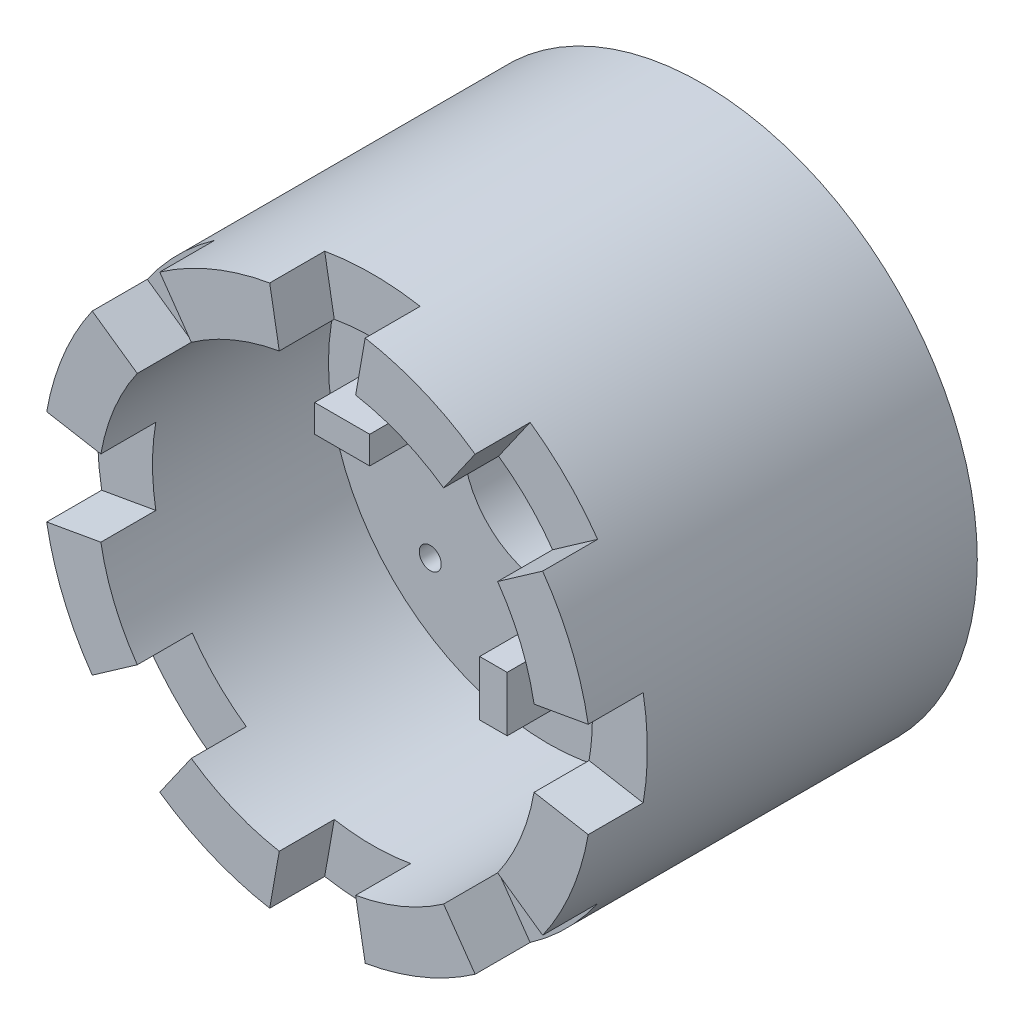
SolidWorks part; units mm, degrees
ref_plane "Alzado" through (0, 0, 0) normal (0, 0, 1) x (1, 0, 0)
ref_plane "Planta" through (0, 0, 0) normal (0, 1, 0) x (1, 0, 0)
ref_plane "Vista lateral" through (0, 0, 0) normal (1, 0, 0) x (0, 0, -1)
sketch "Croquis1" plane through (0, 0, 0) normal (0, 0, 1) x (1, 0, 0)
  circle A0 centre (0, 0) radius 50
  circle A1 centre (0, 0) radius 15.5
  point P4 (0, 0)
  dimension "D1" = 100
  dimension "D2" = 31
extrude "Saliente-Extruir1" add sketch "Croquis1" along normal blind 70
sketch "Croquis2" plane through (0, 0, 70) normal (0, 0, 1) x (1, 0, 0)
  circle A0 centre (0, 0) radius 40
  dimension "D1" = 80
extrude "Cortar-Extruir1" cut sketch "Croquis2" against normal blind 32
sketch "Croquis3" plane through (0, 0, 0) normal (0, 0, -1) x (-1, 0, 0)
  circle A0 centre (0, 0) radius 17.5
  dimension "D1" = 35
extrude "Cortar-Extruir2" cut sketch "Croquis3" against normal blind 10
sketch "Croquis4" plane through (0, 0, 38) normal (0, 0, 1) x (1, 0, 0)
  line L1 (-2.5, 32.5) -> (2.5, 32.5)
  line L2 (-2.5, 32.5) -> (-2.5, 22.5)
  line L3 (-2.5, 22.5) -> (2.5, 22.5)
  line L4 (2.5, 32.5) -> (2.5, 22.5)
  line L5 (-2.5, 32.5) -> (2.5, 22.5) construction
  line L6 (-2.5, 22.5) -> (2.5, 32.5) construction
  line L7 (32.5, -2.5) -> (22.5, -2.5)
  line L8 (32.5, -2.5) -> (32.5, 2.5)
  line L9 (32.5, 2.5) -> (22.5, 2.5)
  line L10 (22.5, -2.5) -> (22.5, 2.5)
  line L11 (32.5, -2.5) -> (22.5, 2.5) construction
  line L12 (32.5, 2.5) -> (22.5, -2.5) construction
  line L13 (2.5, -32.5) -> (-2.5, -32.5)
  line L14 (2.5, -32.5) -> (2.5, -22.5)
  line L15 (2.5, -22.5) -> (-2.5, -22.5)
  line L16 (-2.5, -32.5) -> (-2.5, -22.5)
  line L17 (2.5, -32.5) -> (-2.5, -22.5) construction
  line L18 (2.5, -22.5) -> (-2.5, -32.5) construction
  line L19 (-32.5, -2.5) -> (-22.5, -2.5)
  line L20 (-32.5, -2.5) -> (-32.5, 2.5)
  line L21 (-32.5, 2.5) -> (-22.5, 2.5)
  line L22 (-22.5, -2.5) -> (-22.5, 2.5)
  line L23 (-32.5, -2.5) -> (-22.5, 2.5) construction
  line L24 (-32.5, 2.5) -> (-22.5, -2.5) construction
  circle A0 centre (0, 0) radius 40
  circle A1 centre (0, 0) radius 27.5
  point P4 (0, 27.5)
  point P9 (27.5, 0)
  point P14 (0, -27.5)
  point P19 (-27.5, 0)
  circle M10 centre (0, 0) radius 15.5
  circle M11 centre (0, 0) radius 40
  dimension "D1" = 80
  dimension "D2" = 55
  dimension "D3" = 10
  dimension "D4" = 5
  dimension "D5" = 5
  dimension "D6" = 10
  dimension "D7" = 5
  dimension "D8" = 10
  dimension "D9" = 5
  dimension "D10" = 10
extrude "Cortar-Extruir3" cut sketch "Croquis4" against normal blind 10 contours A1 L9 L8 L7 L14 L13 L16 L19 L20 L21 L2 L1 L4 M11 | L9 A1 L4 L3 L2 L21 L22 L19 L16 L15 L14 L7 L10 M10
sketch "Croquis5" plane through (0, 0, 28) normal (0, 0, 1) x (1, 0, 0)
  line L0 (0, 0) -> (28.2843, 28.2843) construction
  circle A0 centre (21.487, 21.487) radius 2
  circle A1 centre (21.487, -21.487) radius 2
  circle A2 centre (-21.487, -21.487) radius 2
  circle A3 centre (-21.487, 21.487) radius 2
  point P14 (0, 0)
  dimension "D2" = 4
  dimension "D1" = 40
  dimension "D3" = 4
extrude "Cortar-Extruir4" cut sketch "Croquis5" against normal through all
sketch "Croquis6" plane through (0, 0, 0) normal (0, 0, -1) x (-1, 0, 0)
  circle A0 centre (-21.487, 21.487) radius 5
  circle A1 centre (21.487, 21.487) radius 5
  circle A2 centre (21.487, -21.487) radius 5
  circle A3 centre (-21.487, -21.487) radius 5
  point P12 (0, 0)
  dimension "D1" = 10
  dimension "D2" = 4
extrude "Cortar-Extruir5" cut sketch "Croquis6" against normal blind 5
sketch "Croquis7" plane through (0, 0, 70) normal (0, 0, 1) x (1, 0, 0)
  line L0 (0, 0) -> (0, 50)
  line L1 (0, 0) -> (8.6824, 49.2404)
  line L2 (0, 0) -> (-8.6824, 49.2404)
  line L3 (0, 0) -> (40.9576, 28.6788)
  line L4 (0, 0) -> (28.6788, 40.9576)
  line L5 (0, 0) -> (49.2404, -8.6824)
  line L6 (0, 0) -> (49.2404, 8.6824)
  line L7 (0, 0) -> (28.6788, -40.9576)
  line L8 (0, 0) -> (40.9576, -28.6788)
  line L9 (0, 0) -> (-8.6824, -49.2404)
  line L10 (0, 0) -> (8.6824, -49.2404)
  line L11 (0, 0) -> (-40.9576, -28.6788)
  line L12 (0, 0) -> (-28.6788, -40.9576)
  line L13 (0, 0) -> (-49.2404, 8.6824)
  line L14 (0, 0) -> (-49.2404, -8.6824)
  line L15 (0, 0) -> (-28.6788, 40.9576)
  line L16 (0, 0) -> (-40.9576, 28.6788)
  circle A0 centre (0, 0) radius 50 construction
  circle A1 centre (0, 0) radius 40
  circle A2 centre (0, 0) radius 50
  point P27 (0, 0)
  circle M5 centre (0, 0) radius 40
  circle M6 centre (0, 0) radius 50
  dimension "D3" = 100
  dimension "D4" = 80
  dimension "D1" = 10
  dimension "D2" = 10
  dimension "D5" = 8
extrude "Cortar-Extruir6" cut sketch "Croquis7" against normal blind 10 contours L2 L0 M5 M6 | L1 L0 M5 M6 | L4 L3 M5 M6 | L6 L5 M5 M6 | L8 L7 M5 M6 | L16 L15 M5 M6 | L14 L13 M5 M6 | L12 L11 M5 M6 | L10 L9 M5 M6
